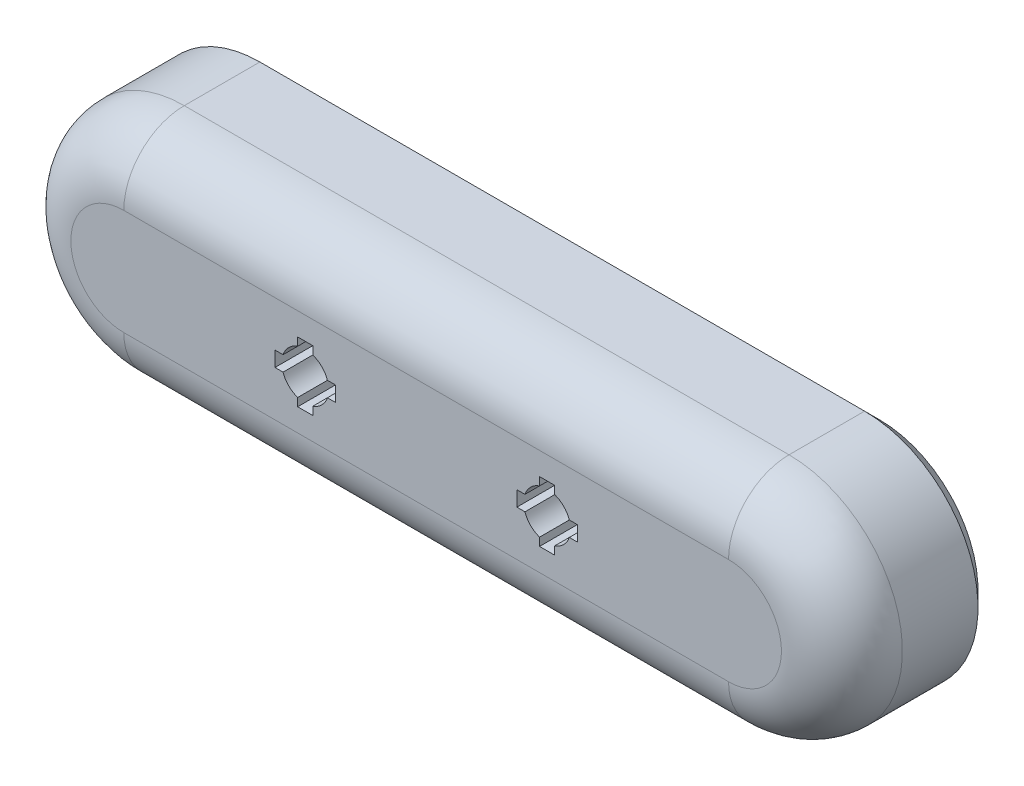
SolidWorks part; units mm, degrees
ref_plane "Front Plane" through (0, 0, 0) normal (0, 0, 1) x (1, 0, 0)
ref_plane "Top Plane" through (0, 0, 0) normal (0, 1, 0) x (1, 0, 0)
ref_plane "Right Plane" through (0, 0, 0) normal (1, 0, 0) x (0, 0, -1)
sketch "Sketch1" plane through (0, 0, 0) normal (0, 0, 1) x (1, 0, 0)
  line L0 (-12, 0) -> (28, 0) construction
  line L1 (-12, 7.5) -> (28, 7.5)
  line L2 (-12, -7.5) -> (28, -7.5)
  line L3 (8, 12.0814) -> (8, -10.8916) construction
  line L4 (-0.5, -2) -> (0.5, -2)
  line L5 (-0.5, -2) -> (-0.5, -1.4671)
  line L6 (-0.5, 2) -> (0.5, 2)
  line L7 (0.5, -2) -> (0.5, -1.4671)
  line L8 (-0.5, -2) -> (0.5, 2) construction
  line L9 (-0.5, 2) -> (0.5, -2) construction
  line L10 (-2, -0.5) -> (-1.4671, -0.5)
  line L11 (-2, -0.5) -> (-2, 0.5)
  line L12 (-2, 0.5) -> (-1.4671, 0.5)
  line L13 (2, -0.5) -> (2, 0.5)
  line L14 (-2, -0.5) -> (2, 0.5) construction
  line L15 (-2, 0.5) -> (2, -0.5) construction
  line L16 (0.5, 1.4671) -> (0.5, 2)
  line L17 (1.4671, 0.5) -> (2, 0.5)
  line L18 (-0.5, 1.4671) -> (-0.5, 2)
  line L19 (1.4671, -0.5) -> (2, -0.5)
  line L20 (18, -0.5) -> (18, 0.5)
  line L21 (18, 0.5) -> (17.4671, 0.5)
  line L22 (16.5, 1.4671) -> (16.5, 2)
  line L23 (16.5, 2) -> (15.5, 2)
  line L24 (15.5, 1.4671) -> (15.5, 2)
  line L25 (14.5329, 0.5) -> (14, 0.5)
  line L26 (14, -0.5) -> (14, 0.5)
  line L27 (14.5329, -0.5) -> (14, -0.5)
  line L28 (15.5, -2) -> (15.5, -1.4671)
  line L29 (16.5, -2) -> (15.5, -2)
  line L30 (16.5, -2) -> (16.5, -1.4671)
  line L31 (18, -0.5) -> (17.4671, -0.5)
  arc A0 (-0.5, 1.4671) -> (-1.4671, 0.5) centre (0, 0) ccw
  arc A1 (-12, 7.5) -> (-12, -7.5) centre (-12, 0) ccw
  arc A2 (28, -7.5) -> (28, 7.5) centre (28, 0) ccw
  arc A3 (-1.4671, -0.5) -> (-0.5, -1.4671) centre (0, 0) ccw
  arc A4 (1.4671, 0.5) -> (0.5, 1.4671) centre (0, 0) ccw
  arc A5 (0.5, -1.4671) -> (1.4671, -0.5) centre (0, 0) ccw
  arc A6 (16.5, 1.4671) -> (17.4671, 0.5) centre (16, 0) cw
  arc A7 (14.5329, 0.5) -> (15.5, 1.4671) centre (16, 0) cw
  arc A8 (15.5, -1.4671) -> (14.5329, -0.5) centre (16, 0) cw
  arc A9 (17.4671, -0.5) -> (16.5, -1.4671) centre (16, 0) cw
  point P5 (8, 0)
  dimension "D1" = 3.1
  dimension "D2" = 15
  dimension "D3" = 40
  dimension "D4" = 1
  dimension "D5" = 8
  dimension "D6" = 1
  dimension "D7" = 4
  dimension "D8" = 4
extrude "Boss-Extrude1" add sketch "Sketch1" along normal blind 10
fillet "Fillet1" radius 4 4 edges at (-19.5, 0, 10) (8, 7.5, 10) (35.5, 0, 10) (8, -7.5, 10)
chamfer "Chamfer1" distance 1 angle 45 4 edges at (8, 7.5, 0) (35.5, 0, 0) (-19.5, 0, 0) (8, -7.5, 0)
